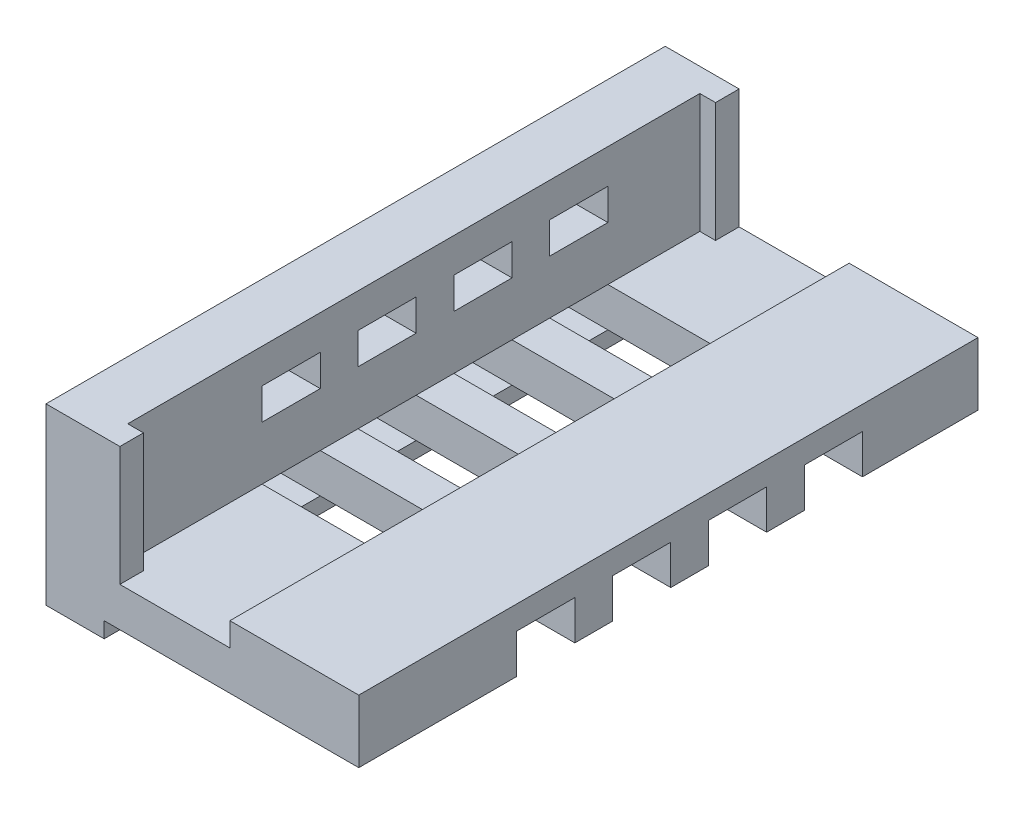
SolidWorks part; units mm, degrees
ref_plane "Plano frontal" through (0, 0, 0) normal (0, 0, 1) x (1, 0, 0)
ref_plane "Plano superior" through (0, 0, 0) normal (0, 1, 0) x (1, 0, 0)
ref_plane "Plano direito" through (0, 0, 0) normal (1, 0, 0) x (0, 0, -1)
sketch "Esboço1" plane through (0, 0, 0) normal (0, 0, 1) x (1, 0, 0)
  line L0 (0, 0) -> (0, 10.1)
  line L1 (0, 10.1) -> (3.7, 10.1)
  line L2 (3.7, 10.1) -> (3.7, 2.5)
  line L3 (3.7, 2.5) -> (11.7, 2.5)
  line L4 (11.7, 2.5) -> (11.7, 4)
  line L5 (11.7, 4) -> (19.9, 4)
  line L6 (19.9, 4) -> (19.9, 0)
  line L7 (19.9, 0) -> (3.7, 0)
  line L8 (3.7, 0) -> (3.7, -1)
  line L9 (3.7, -1) -> (0, -1)
  line L10 (0, -1) -> (0, 0)
  dimension "D1" = 3.7
  dimension "D2" = 2.5
  dimension "D3" = 10.1
  dimension "D4" = 16.2
  dimension "D5" = 8
  dimension "D6" = 1.5
  dimension "D7" = 1
extrude "Ressalto-extrusão1" add sketch "Esboço1" against normal blind 39.4
sketch "Esboço2" plane through (19.9, 0, 0) normal (1, 0, 0) x (0, 0, -1)
  line L0 (39.4, 0) -> (0, 0) construction
  line L1 (10.05, 0) -> (13.75, 0)
  line L2 (10.05, 0) -> (10.05, 2.5)
  line L3 (10.05, 2.5) -> (13.75, 2.5)
  line L4 (13.75, 0) -> (13.75, 2.5)
  line L5 (39.4, 2.5) -> (0, 2.5) construction
  point P8 (11.9, 0)
  dimension "D1" = 3.7
  dimension "D2" = 11.9
extrude "Corte-extrusão1" cut sketch "Esboço2" against normal through all
sketch "Esboço3" plane through (3.7, 0, 0) normal (1, 0, 0) x (0, 0, -1)
  line L1 (13.75, 5.9145) -> (10.05, 5.9145)
  line L2 (13.75, 5.9145) -> (13.75, 7.9145)
  line L3 (13.75, 7.9145) -> (10.05, 7.9145)
  line L4 (10.05, 5.9145) -> (10.05, 7.9145)
  dimension "D1" = 2
extrude "Corte-extrusão2" cut sketch "Esboço3" against normal blind 10
pattern_linear "Padrão linear1" count 4 spacing 6.1 along (0, 0, -1) of "Corte-extrusão1", "Corte-extrusão2"
sketch "Esboço5" plane through (3.7, 0, 0) normal (1, 0, 0) x (0, 0, -1)
  line L0 (10.05, 2.5) -> (0, 2.5) construction
  line L1 (0, 10.1) -> (1.5, 10.1)
  line L2 (0, 10.1) -> (0, 2.5)
  line L3 (0, 2.5) -> (1.5, 2.5)
  line L4 (1.5, 10.1) -> (1.5, 2.5)
  dimension "D1" = 1.5
extrude "Ressalto-extrusão2" add sketch "Esboço5" along normal blind 1
ref_plane "Plano2" through (0, 0, -19.7) normal (0, 0, 1) x (1, 0, 0)
mirror "Espelhar1" about plane through (0, 0, -19.7) normal (0, 0, 1) of "Ressalto-extrusão2"
